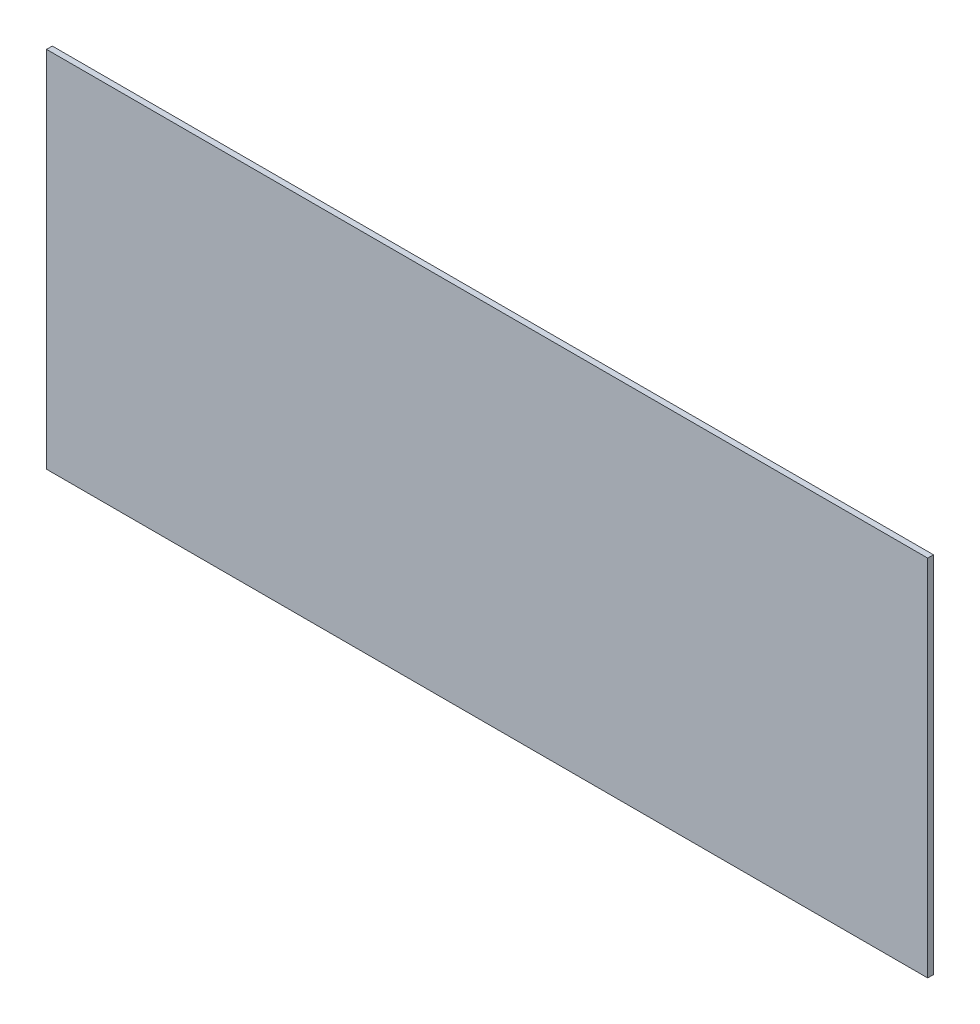
SolidWorks part; units mm, degrees
ref_plane "Front Plane" through (0, 0, 0) normal (0, 0, 1) x (1, 0, 0)
ref_plane "Top Plane" through (0, 0, 0) normal (0, 1, 0) x (1, 0, 0)
ref_plane "Right Plane" through (0, 0, 0) normal (1, 0, 0) x (0, 0, -1)
ref_plane "Plane1" through (0, 0, 0) normal (0, 0, -1) x (-1, 0, 0)
sketch "Sketch1" plane through (0, 0, 0) normal (0, 0, -1) x (-1, 0, 0)
  line L0 (-114, -221.439) -> (-114, -321.439)
  line L1 (-114, -321.439) -> (191, -321.439)
  line L2 (191, -321.439) -> (191, -221.439)
  line L3 (191, -221.439) -> (-114, -221.439)
  dimension "D1" = 305
  dimension "D2" = 100
extrude "Boss-Extrude1" add sketch "Sketch1" against normal blind 2
sketch "Sketch2" plane through (0, -221.439, 0) normal (0, 1, 0) x (1, 0, 0)
  line L4 (114, 0) -> (-191, 0)
  line L5 (-191, 0) -> (-191, -2)
  line L6 (-191, -2) -> (114, -2)
  line L7 (114, -2) -> (114, 0)
  line L8 (114, 0) -> (-191, 0)
  line L9 (-191, 0) -> (-191, -2)
  line L10 (-191, -2) -> (114, -2)
  line L11 (114, -2) -> (114, 0)
  dimension "D1" = 0
extrude "Boss-Extrude2" add sketch "Sketch2" along normal up to surface (25.8598 mm away)
